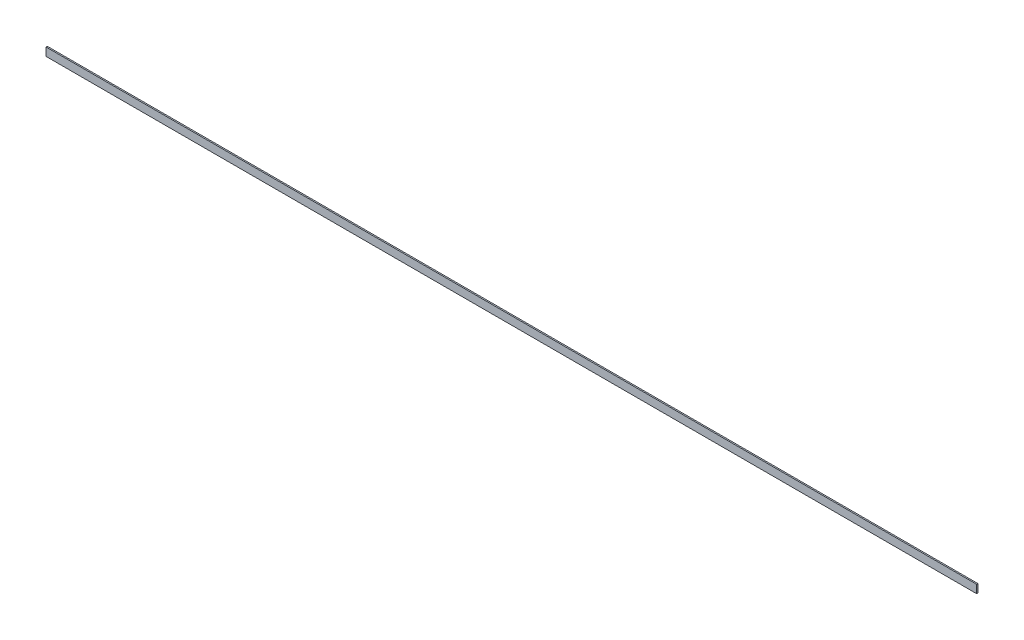
SolidWorks part; units mm, degrees
ref_plane "Front Plane" through (0, 0, 0) normal (0, 0, 1) x (1, 0, 0)
ref_plane "Top Plane" through (0, 0, 0) normal (0, 1, 0) x (1, 0, 0)
ref_plane "Right Plane" through (0, 0, 0) normal (1, 0, 0) x (0, 0, -1)
sketch "Sketch1" plane through (0, 0, 0) normal (0, 0, 1) x (1, 0, 0)
  line L0 (411.2763, 43.7964) -> (-173.2036, 43.7964) construction
  line L1 (304.2233, 39.2964) -> (-208.5779, 39.2964)
  line L2 (304.2233, 39.2964) -> (304.2233, 43.7964)
  line L3 (304.2233, 43.7964) -> (-208.5779, 43.7964)
  line L4 (-208.5779, 39.2964) -> (-208.5779, 43.7964)
  line L5 (411.2763, 39.2964) -> (-173.2036, 39.2964) construction
  line L7 (-208.5779, 26.5502) -> (-208.5945, 59.6464) construction
  line L8 (-210.0779, 26.5502) -> (-207.0779, 26.5502) construction
  line L9 (-199.9814, 59.6464) -> (-217.2076, 59.6464) construction
extrude "Boss-Extrude1" add sketch "Sketch1" along normal blind 0.7
